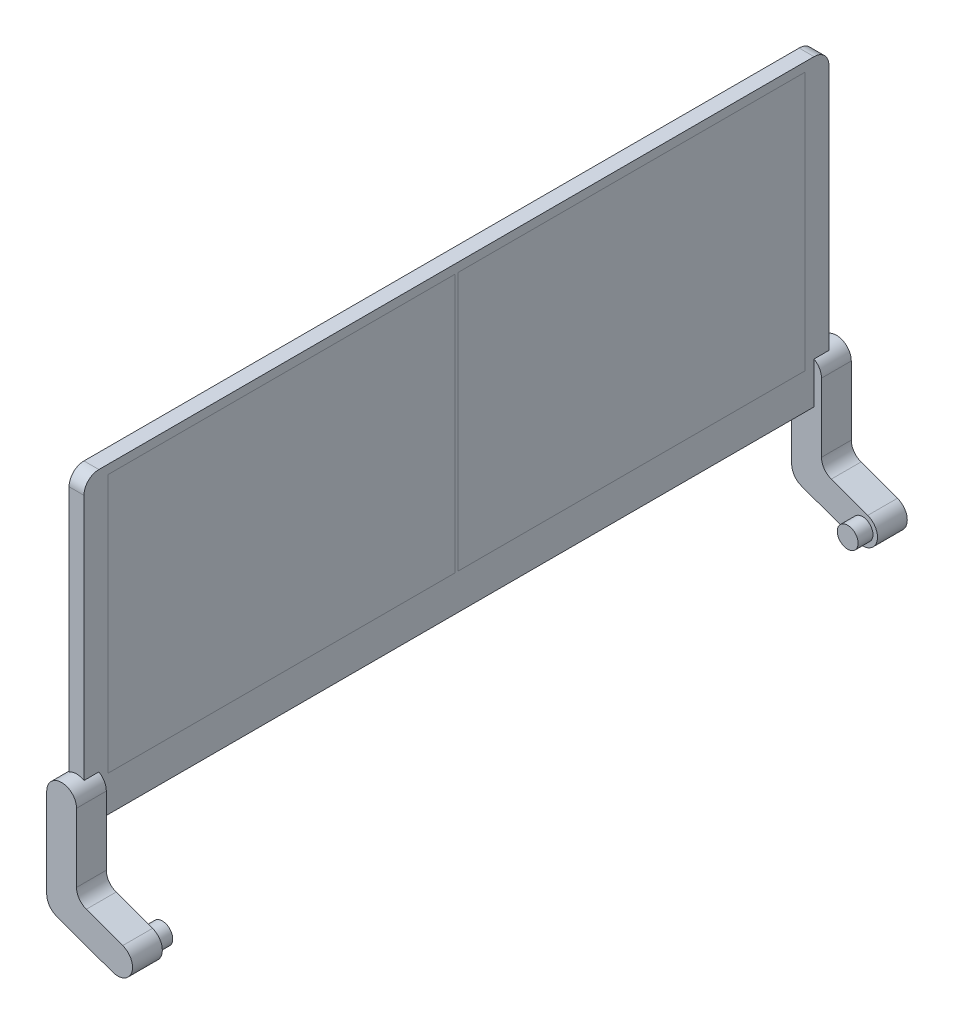
SolidWorks part; units mm, degrees
ref_plane "Ön Düzlem" through (0, 0, 0) normal (0, 0, 1) x (1, 0, 0)
ref_plane "Üst Düzlem" through (0, 0, 0) normal (0, 1, 0) x (1, 0, 0)
ref_plane "Sağ Düzlem" through (0, 0, 0) normal (1, 0, 0) x (0, 0, -1)
sketch "Çizim1" plane through (0, 0, 0) normal (1, 0, 0) x (0, 0, -1)
  line L0 (0, 0) -> (0, 101.8) construction
  line L1 (-120, 101.8) -> (120, 101.8)
  line L2 (-125, 96.8) -> (-125, 0)
  line L3 (-125, 0) -> (125, 0)
  line L4 (125, 96.8) -> (125, 0)
  line L5 (115, 14) -> (2.5, 14)
  line L6 (-115, 96.8) -> (-2.5, 96.8)
  line L7 (-115, 96.8) -> (-115, 14)
  line L8 (-115, 14) -> (-2.5, 14)
  line L9 (-2.5, 96.8) -> (-2.5, 14)
  line L10 (2.5, 96.8) -> (2.5, 14)
  line L11 (115, 96.8) -> (2.5, 96.8)
  line L12 (115, 96.8) -> (115, 14)
  arc A0 (120, 101.8) -> (125, 96.8) centre (120, 96.8) cw
  arc A1 (-120, 101.8) -> (-125, 96.8) centre (-120, 96.8) ccw
  point P17 (125, 101.8)
  dimension "D7" = 5
  dimension "D1" = 250
  dimension "D2" = 101.8
  dimension "D3" = 5
  dimension "D4" = 14
  dimension "D5" = 10
  dimension "D6" = 5
extrude "Yükseklik-Ekstrüzyon1" add sketch "Çizim1" against normal blind 5
chamfer "Pah1" distance 2 angle 45 8 edges at (0, 55.4, -2.5) (0, 96.8, -58.75) (0, 55.4, -115) (0, 14, -58.75) (0, 55.4, 115) (0, 96.8, 58.75) (0, 55.4, 2.5) (0, 14, 58.75)
sketch "Çizim2" plane through (0, 0, 125) normal (0, 0, 1) x (1, 0, 0)
  line L0 (-5, 0) -> (0, 0)
  line L1 (0, 0) -> (-5, 1.8199)
  line L2 (-5, 96.8) -> (-5, 0) construction
  line L3 (-5, 1.8199) -> (-5, 0)
  line L4 (0, 96.8) -> (0, 0) construction
  dimension "D1" = 110
extrude "Kes-Ekstrüzyon1" cut sketch "Çizim2" against normal through all
sketch "Çizim3" plane through (0, 0, 125) normal (0, 0, 1) x (1, 0, 0)
  line L0 (-2.5, 9.6) -> (-2.5, -20.4) construction
  line L1 (-2.5, -20.4) -> (16.2939, -27.2404) construction
  line L2 (-7.5, 9.6) -> (-7.5, -20.4)
  line L3 (-4.2101, -25.0985) -> (14.5838, -31.9389)
  line L4 (2.5, 9.6) -> (2.5, -13.3979)
  line L5 (5.7899, -18.0964) -> (18.004, -22.5419)
  line L6 (-7.5, 9.6) -> (-7.5, -23.901) construction
  line L7 (-7.5, -23.901) -> (14.5838, -31.9389) construction
  line L8 (2.5, 9.6) -> (2.5, -16.899) construction
  line L9 (2.5, -16.899) -> (18.004, -22.5419) construction
  arc A0 (-7.5, 9.6) -> (2.5, 9.6) centre (-2.5, 9.6) cw
  arc A1 (14.5838, -31.9389) -> (18.004, -22.5419) centre (16.2939, -27.2404) ccw
  arc A2 (-7.5, -20.4) -> (-4.2101, -25.0985) centre (-2.5, -20.4) ccw
  arc A3 (2.5, -13.3979) -> (5.7899, -18.0964) centre (7.5, -13.3979) ccw
  dimension "D8" = 5
  dimension "D9" = 5
  dimension "D1" = 30
  dimension "D2" = 20
  dimension "D3" = 2.5
  dimension "D4" = 92.2
  dimension "D5" = 110
  dimension "D6" = 5
  dimension "D7" = 5
extrude "Yükseklik-Ekstrüzyon2" add sketch "Çizim3" along normal mid plane 10 separate body
sketch "Çizim4" plane through (0, 0, 120) normal (0, 0, -1) x (-1, 0, 0)
  circle A0 centre (-16.2939, -27.2404) radius 3.5
  dimension "D1" = 7
extrude "Yükseklik-Ekstrüzyon3" add sketch "Çizim4" along normal blind 5
mirror "Aynalama1" about plane through (0, 0, 0) normal (0, 0, 1) of bodies 104
sketch "Çizim5" plane through (0, 0, 0) normal (1, 0, 0) x (0, 0, -1)
  line L0 (0.5, 98.8) -> (117, 98.8) construction
  line L1 (-0.5, 12) -> (-117, 12) construction
  line L2 (-117, 12) -> (-117, 98.8) construction
  line L3 (-117, 98.8) -> (-0.5, 98.8) construction
  line L4 (-0.5, 98.8) -> (-0.5, 12) construction
  line L5 (117, 12) -> (0.5, 12) construction
  line L6 (0.5, 12) -> (0.5, 98.8) construction
  line L7 (117, 98.8) -> (117, 12) construction
  line L8 (117, 98.8) -> (117, 12)
  line L9 (0.5, 98.8) -> (117, 98.8)
  line L10 (0.5, 12) -> (0.5, 98.8)
  line L11 (117, 12) -> (0.5, 12)
  line L12 (-0.5, 98.8) -> (-0.5, 12)
  line L13 (-117, 98.8) -> (-0.5, 98.8)
  line L14 (-117, 12) -> (-117, 98.8)
  line L15 (-0.5, 12) -> (-117, 12)
extrude "Yükseklik-Ekstrüzyon4" add sketch "Çizim5" against normal blind 1 separate body
